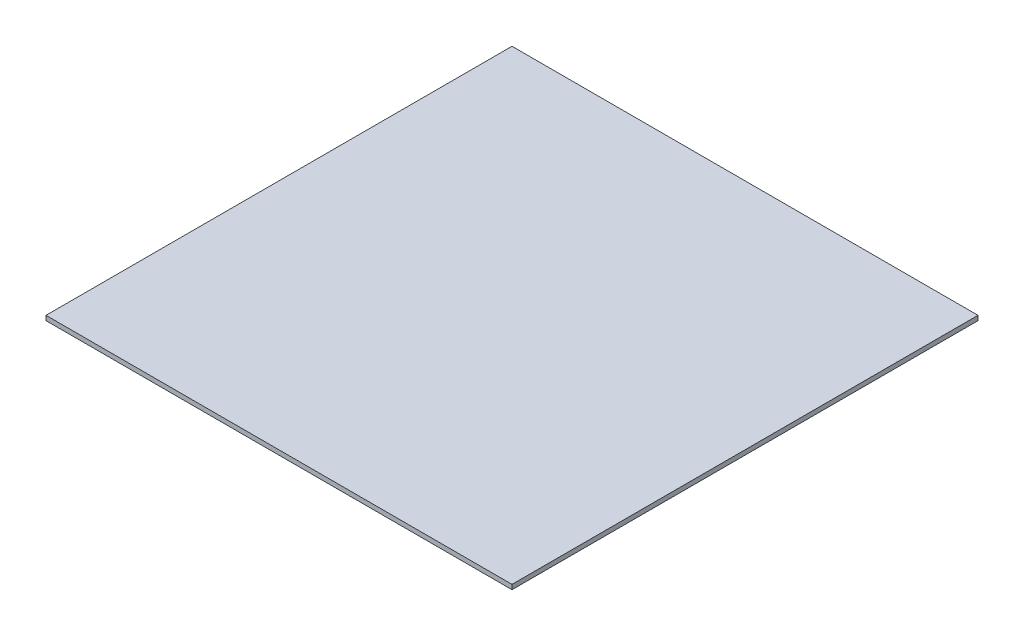
SolidWorks part; units mm, degrees
material "6061-T6 (SS)"
ref_plane "Front Plane" through (0, 0, 0) normal (0, 0, 1) x (1, 0, 0)
ref_plane "Top Plane" through (0, 0, 0) normal (0, 1, 0) x (1, 0, 0)
ref_plane "Right Plane" through (0, 0, 0) normal (1, 0, 0) x (0, 0, -1)
sketch "Sketch1" plane through (0, 0, 0) normal (0, 1, 0) x (1, 0, 0)
  line L1 (0, 0) -> (-637.601, 0)
  line L2 (0, 0) -> (0, 637.601)
  line L3 (0, 637.601) -> (-637.601, 637.601)
  line L4 (-637.601, 0) -> (-637.601, 637.601)
  dimension "D1" = 637.601
  dimension "D2" = 637.601
extrude "Boss-Extrude1" add sketch "Sketch1" along normal blind 6.35
equation "\"D2@Sketch1\"=\"D1@Sketch1\""
